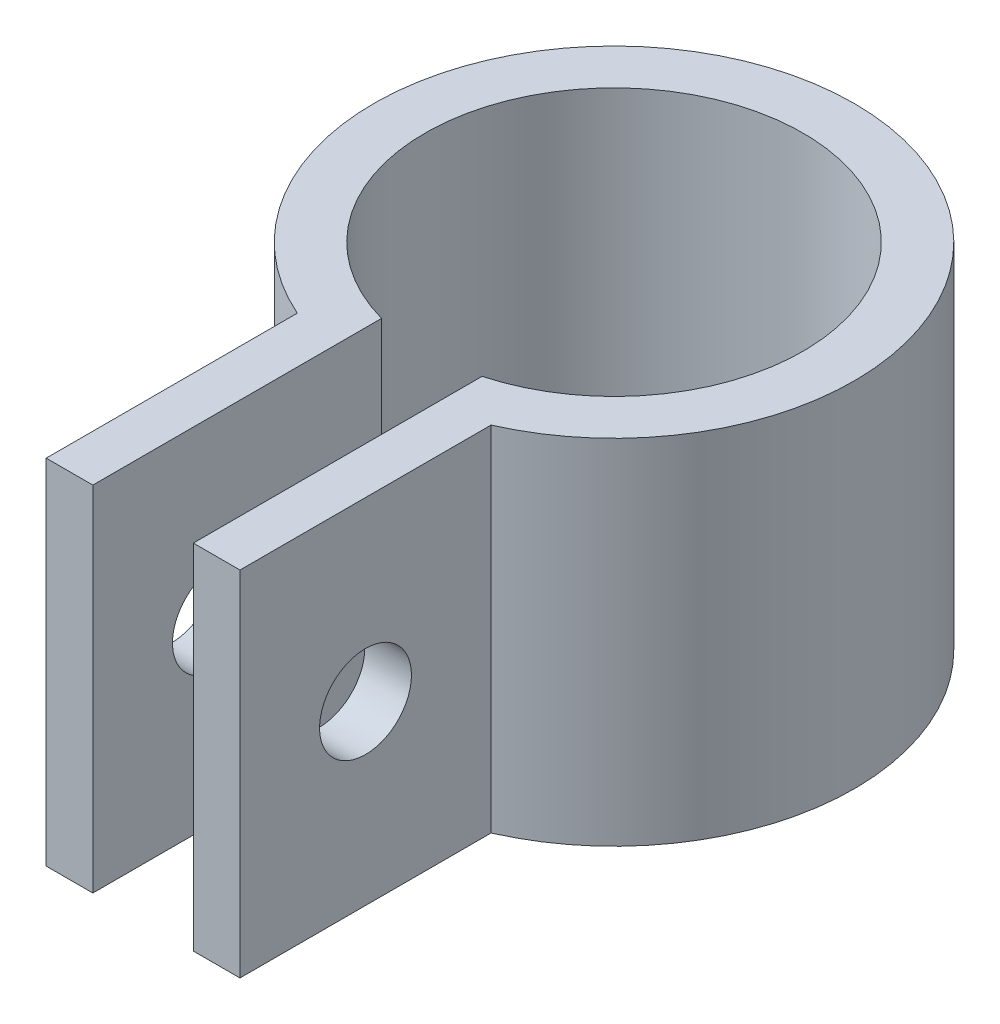
SolidWorks part; units mm, degrees
ref_plane "前视基准面" through (0, 0, 0) normal (0, 0, 1) x (1, 0, 0)
ref_plane "上视基准面" through (0, 0, 0) normal (0, 1, 0) x (1, 0, 0)
ref_plane "右视基准面" through (0, 0, 0) normal (1, 0, 0) x (0, 0, -1)
sketch "草图1" plane through (0, 0, 0) normal (0, 1, 0) x (1, 0, 0)
  circle A0 centre (0, 0) radius 6.8
extrude "凸台-拉伸1" add sketch "草图1" along normal blind 10
sketch "草图3" plane through (0, 0, 0) normal (0, 1, 0) x (1, 0, 0)
  line L0 (0, 0) -> (-6.9848, -6.3827) construction
  line L2 (2.7423, 0.045) -> (-2.7423, 0.045)
  line L3 (2.7423, 0.045) -> (2.7423, -13.3292)
  line L4 (2.7423, -13.3292) -> (-2.7423, -13.3292)
  line L5 (-2.7423, 0.045) -> (-2.7423, -13.3292)
  line L6 (2.7423, 0.045) -> (-2.7423, -13.3292) construction
  line L7 (2.7423, -13.3292) -> (-2.7423, 0.045) construction
extrude "凸台-拉伸2" add sketch "草图3" along normal blind 10
sketch "草图2" plane through (0, 10, 0) normal (0, 1, 0) x (1, 0, 0)
  circle A0 centre (0, 0) radius 5.35
extrude "切除-拉伸1" cut sketch "草图2" against normal blind 10
sketch "草图4" plane through (0, 0, 0) normal (0, 1, 0) x (1, 0, 0)
  line L0 (-2.7423, -13.3292) -> (2.7423, -13.3292) construction
  line L1 (-1.422, -22.1142) -> (1.422, -22.1142)
  line L2 (-1.422, -22.1142) -> (-1.422, -4.5442)
  line L3 (-1.422, -4.5442) -> (1.422, -4.5442)
  line L4 (1.422, -22.1142) -> (1.422, -4.5442)
  line L5 (-1.422, -22.1142) -> (1.422, -4.5442) construction
  line L6 (-1.422, -4.5442) -> (1.422, -22.1142) construction
  point P0 (0, -13.3292)
extrude "切除-拉伸2" cut sketch "草图4" along normal blind 10
sketch "草图5" plane through (2.7423, 0, 0) normal (1, 0, 0) x (0, 0, -1)
  circle A0 centre (-9.7759, 5) radius 1.3
extrude "切除-拉伸3" cut sketch "草图5" against normal blind 10
